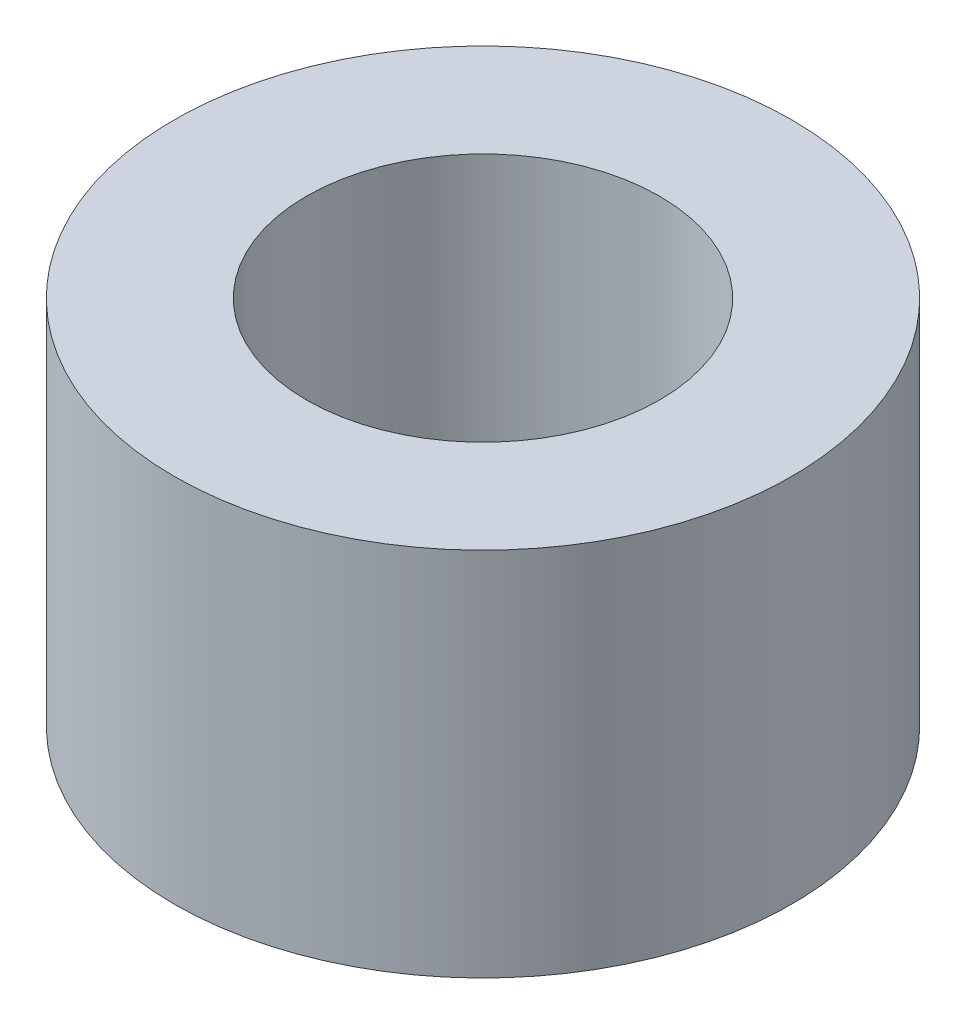
SolidWorks part; units mm, degrees
ref_plane "Front" through (0, 0, 0) normal (0, 0, 1) x (1, 0, 0)
ref_plane "Top" through (0, 0, 0) normal (0, 1, 0) x (1, 0, 0)
ref_plane "Right" through (0, 0, 0) normal (1, 0, 0) x (0, 0, -1)
sketch "Sketch1" plane through (0, 0, 0) normal (0, 1, 0) x (1, 0, 0)
  circle A0 centre (0, 0) radius 5.334
  circle A1 centre (0, 0) radius 3.05
  dimension "D1" = 10.668
  dimension "D2" = 6.1
extrude "Boss-Extrude1" add sketch "Sketch1" along normal blind 6.4
